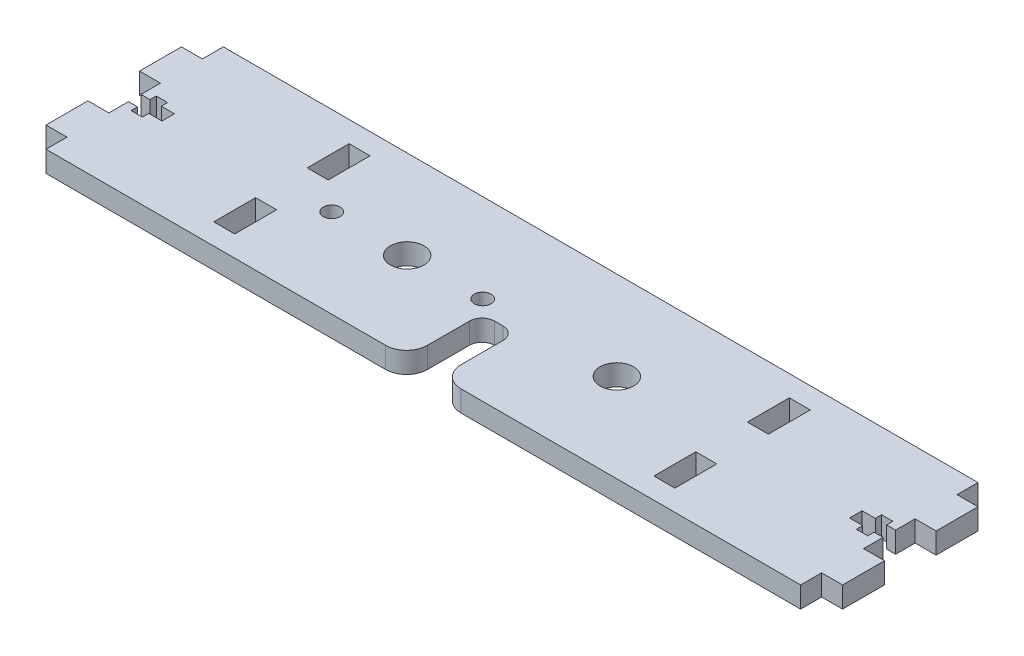
SolidWorks part; units mm, degrees
ref_plane "前视基准面" through (0, 0, 0) normal (0, 0, 1) x (1, 0, 0)
ref_plane "上视基准面" through (0, 0, 0) normal (0, 1, 0) x (1, 0, 0)
ref_plane "右视基准面" through (0, 0, 0) normal (1, 0, 0) x (0, 0, -1)
sketch "草图1" plane through (0, 0, 0) normal (0, 1, 0) x (1, 0, 0)
  line L0 (-92.4719, 31.4954) -> (-92.4719, -54.1143) construction
  line L1 (-87.4719, -35.048) -> (-6.4719, -35.048)
  line L2 (-87.4719, -35.048) -> (-87.4719, -30.048)
  line L3 (-87.4719, 7.252) -> (92.5281, 7.252)
  line L4 (92.5281, -35.048) -> (92.5281, -30.048)
  line L5 (-52.4719, 44.156) -> (-52.4719, -55.722) construction
  line L6 (52.5281, 46.9695) -> (52.5281, -58.9374) construction
  line L7 (-47.4719, 44.156) -> (-47.4719, -50.497) construction
  line L8 (57.5281, 45.5628) -> (57.5281, -55.722) construction
  line L9 (-112.1367, -13.898) -> (112.1367, -13.898) construction
  line L10 (2.5281, 58.9374) -> (2.5281, -55.722) construction
  line L11 (-22.4719, 24.3501) -> (-22.4719, -50.497) construction
  line L12 (-87.4719, 2.252) -> (-92.4719, 2.252)
  line L13 (-87.4719, -20.048) -> (-87.4719, -15.389)
  line L14 (-87.4719, -7.748) -> (-92.4719, -7.748)
  line L15 (-92.4719, 2.252) -> (-92.4719, -7.748)
  line L16 (-87.4719, -20.048) -> (-92.4719, -20.048)
  line L17 (92.5281, 2.252) -> (92.5281, 7.252)
  line L18 (-87.4719, -30.048) -> (-92.4719, -30.048)
  line L19 (-92.4719, -20.048) -> (-92.4719, -30.048)
  line L20 (92.5281, 2.252) -> (97.5281, 2.252)
  line L21 (92.5281, -20.048) -> (92.5281, -15.389)
  line L22 (92.5281, -7.748) -> (97.5281, -7.748)
  line L23 (97.5281, 2.252) -> (97.5281, -7.748)
  line L24 (92.5281, -20.048) -> (97.5281, -20.048)
  line L25 (11.5281, -35.048) -> (92.5281, -35.048)
  line L26 (92.5281, -30.048) -> (97.5281, -30.048)
  line L27 (97.5281, -20.048) -> (97.5281, -30.048)
  line L28 (27.5281, 21.3922) -> (27.5281, -50.497) construction
  line L29 (-87.4719, 2.252) -> (-87.4719, 7.252)
  line L30 (-52.4719, 2.252) -> (-47.4719, 2.252)
  line L31 (-52.4719, 2.252) -> (-52.4719, -7.748)
  line L32 (-52.4719, -7.748) -> (-47.4719, -7.748)
  line L33 (-47.4719, 2.252) -> (-47.4719, -7.748)
  line L34 (-52.4719, -20.048) -> (-47.4719, -20.048)
  line L35 (-52.4719, -20.048) -> (-52.4719, -30.048)
  line L36 (-52.4719, -30.048) -> (-47.4719, -30.048)
  line L37 (-47.4719, -20.048) -> (-47.4719, -30.048)
  line L38 (52.5281, -20.048) -> (57.5281, -20.048)
  line L39 (52.5281, -20.048) -> (52.5281, -30.048)
  line L40 (52.5281, -30.048) -> (57.5281, -30.048)
  line L41 (57.5281, -20.048) -> (57.5281, -30.048)
  line L42 (57.5281, -7.748) -> (52.5281, -7.748)
  line L43 (57.5281, -7.748) -> (57.5281, 2.252)
  line L44 (57.5281, 2.252) -> (52.5281, 2.252)
  line L45 (52.5281, -7.748) -> (52.5281, 2.252)
  line L46 (-87.4719, -12.398) -> (-85.3219, -12.398)
  line L47 (6.5281, -30.048) -> (6.5281, -20.048)
  line L48 (3.5281, -17.048) -> (1.5281, -17.048)
  line L49 (-1.4719, -30.048) -> (-1.4719, -20.048)
  line L50 (-79.4719, -12.398) -> (-79.4719, -15.389)
  line L51 (-79.4719, -15.389) -> (-82.6219, -15.389)
  line L52 (-87.4719, -12.398) -> (-87.4719, -7.748)
  line L53 (-85.3219, -15.389) -> (-85.3219, -16.898)
  line L54 (-85.3219, -10.898) -> (-82.6219, -10.898)
  line L55 (-85.3219, -10.898) -> (-85.3219, -12.398)
  line L56 (-85.3219, -16.898) -> (-82.6219, -16.898)
  line L57 (-82.6219, -10.898) -> (-82.6219, -12.398)
  line L58 (-85.3219, -15.389) -> (-87.4719, -15.389)
  line L59 (87.6781, -15.389) -> (87.6781, -16.898)
  line L60 (90.3781, -15.389) -> (90.3781, -16.898)
  line L61 (90.3781, -15.389) -> (92.5281, -15.389)
  line L62 (-82.6219, -15.389) -> (-82.6219, -16.898)
  line L63 (-82.6219, -12.398) -> (-79.4719, -12.398)
  line L64 (87.6781, -10.898) -> (87.6781, -12.398)
  line L65 (90.3781, -10.898) -> (90.3781, -12.398)
  line L66 (90.3781, -16.898) -> (87.6781, -16.898)
  line L67 (84.5281, -12.398) -> (84.5281, -15.389)
  line L68 (84.5281, -15.389) -> (87.6781, -15.389)
  line L69 (87.6781, -12.398) -> (84.5281, -12.398)
  line L70 (90.3781, -10.898) -> (87.6781, -10.898)
  line L71 (92.5281, -12.398) -> (90.3781, -12.398)
  line L72 (92.5281, -12.398) -> (92.5281, -7.748)
  circle A0 centre (-22.4719, -13.898) radius 4
  circle A1 centre (27.5281, -13.898) radius 4
  circle A2 centre (-40.4719, -13.898) radius 2
  circle A3 centre (-4.4719, -13.898) radius 2
  arc A4 (11.5281, -35.048) -> (6.5281, -30.048) centre (11.5281, -30.048) cw
  arc A5 (-6.4719, -35.048) -> (-1.4719, -30.048) centre (-6.4719, -30.048) ccw
  arc A6 (6.5281, -20.048) -> (3.5281, -17.048) centre (3.5281, -20.048) ccw
  arc A7 (1.5281, -17.048) -> (-1.4719, -20.048) centre (1.5281, -20.048) ccw
  point P68 (6.5281, -35.048)
  point P73 (6.5281, -17.048)
  point P79 (-83.9719, -13.898)
  dimension "D22" = 18
  dimension "D32" = 18
  dimension "D35" = 5
  dimension "D36" = 3
  dimension "D2" = 42.3
  dimension "D3" = 5
  dimension "D4" = 5
  dimension "D5" = 5
  dimension "D6" = 21.15
  dimension "D7" = 90
  dimension "D8" = 50
  dimension "D9" = 50
  dimension "D10" = 25
  dimension "D11" = 10
  dimension "D12" = 10
  dimension "D13" = 5
  dimension "D14" = 5
  dimension "D15" = 5
  dimension "D16" = 5
  dimension "D17" = 10
  dimension "D18" = 10
  dimension "D19" = 5
  dimension "D20" = 5
  dimension "D21" = 25
  dimension "D23" = 18
  dimension "D24" = 10
  dimension "D25" = 5
  dimension "D26" = 5
  dimension "D27" = 10
  dimension "D28" = 5
  dimension "D29" = 10
  dimension "D30" = 5
  dimension "D31" = 10
  dimension "D33" = 4
  dimension "D34" = 4
  dimension "D37" = 1.5
  dimension "D38" = 3.5
  dimension "D39" = 8
  dimension "D40" = 2.7
  dimension "D41" = 1.5
  dimension "D42" = 2.7
  dimension "D43" = 1.509
  dimension "D44" = 3.15
  dimension "D45" = 2.15
  dimension "D46" = 6
extrude "凸台-拉伸1" add sketch "草图1" along normal blind 5
